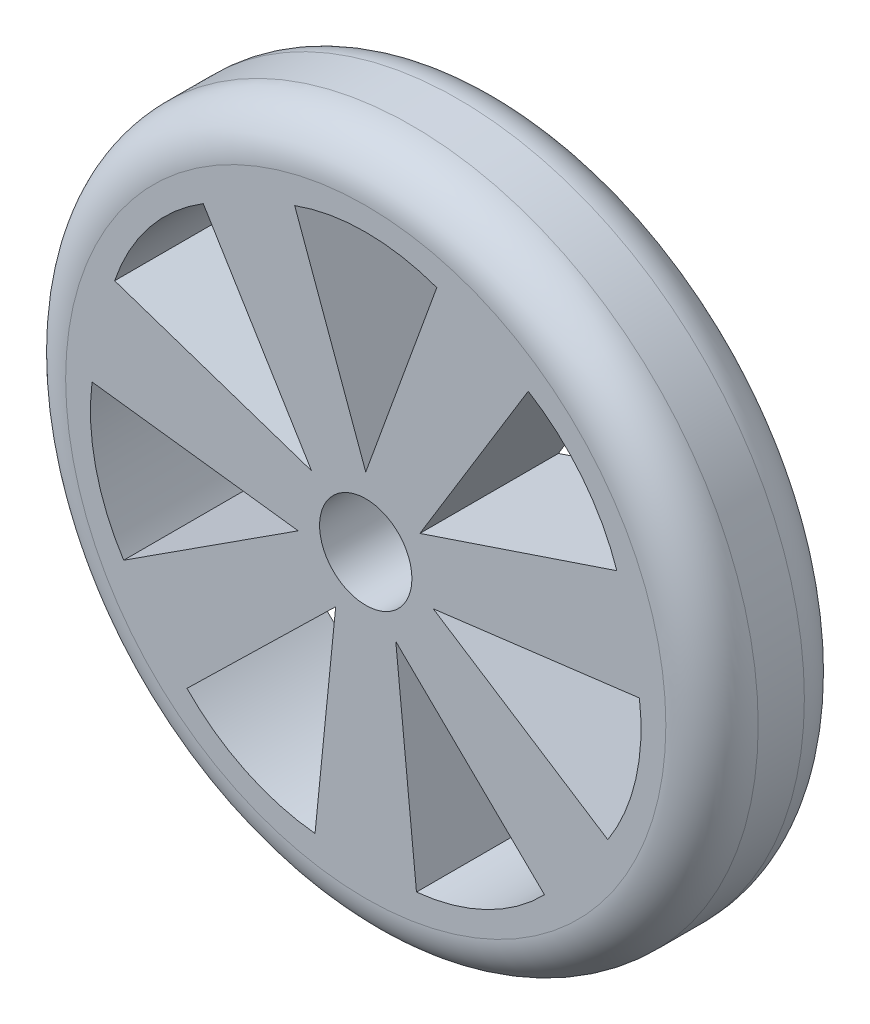
SolidWorks part; units mm, degrees
ref_plane "Front Plane" through (0, 0, 0) normal (0, 0, 1) x (1, 0, 0)
ref_plane "Top Plane" through (0, 0, 0) normal (0, 1, 0) x (1, 0, 0)
ref_plane "Right Plane" through (0, 0, 0) normal (1, 0, 0) x (0, 0, -1)
sketch "Sketch1" plane through (0, 0, 0) normal (0, 0, 1) x (1, 0, 0)
  circle A0 centre (0, 0) radius 10
  circle A1 centre (0, 0) radius 75
  dimension "D1" = 20
  dimension "D2" = 150
extrude "Boss-Extrude1" add sketch "Sketch1" along normal blind 30
sketch "Sketch2" plane through (0, 0, 30) normal (0, 0, 1) x (1, 0, 0)
  line L0 (0, 15) -> (-15.3909, 57.2862)
  line L1 (15.3909, 57.2862) -> (0, 15)
  line L2 (0, 15) -> (0, 0) construction
  arc A0 (-15.3909, 57.2862) -> (15.3909, 57.2862) centre (0, 15) cw
  point P2 (0, 0)
  point P4 (0, 0)
  point P5 (-20.6155, 56.3321)
  dimension "D2" = 45
  dimension "D1" = 40
  dimension "D3" = 15
extrude "Cut-Extrude1" cut sketch "Sketch2" against normal through all
fillet "Fillet1" radius 10 2 edges at (75, 0, 0) (75, 0, 30)
pattern_circular "CirPattern1" count 7 over 360 about axis through (0, 0, 0) along (0, 0, 1) of "Cut-Extrude1"
